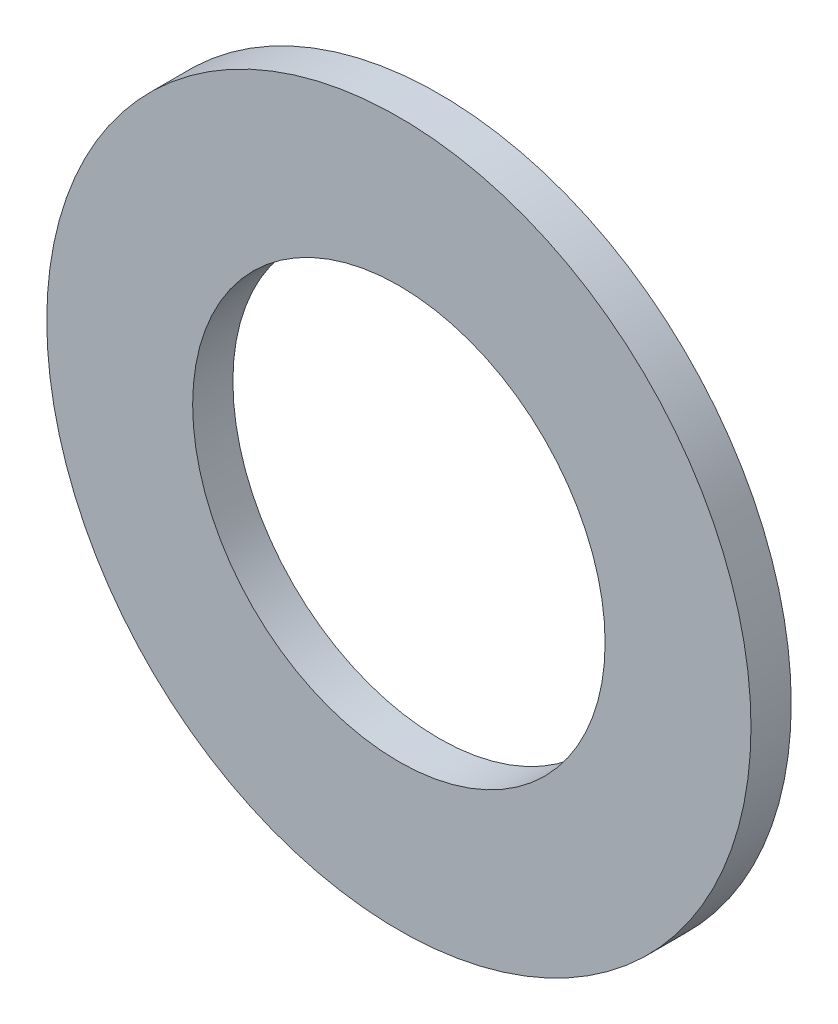
SolidWorks part; units mm, degrees
material "ABS"
ref_plane "Front Plane" through (0, 0, 0) normal (0, 0, 1) x (1, 0, 0)
ref_plane "Top Plane" through (0, 0, 0) normal (0, 1, 0) x (1, 0, 0)
ref_plane "Right Plane" through (0, 0, 0) normal (1, 0, 0) x (0, 0, -1)
sketch "Sketch1" plane through (0, 0, 0) normal (0, 0, 1) x (1, 0, 0)
  circle A0 centre (0, 0) radius 4.1
  circle A1 centre (0, 0) radius 7
  dimension "D1" = 8.2
  dimension "D2" = 14
extrude "Boss-Extrude1" add sketch "Sketch1" along normal blind 0.8
equation "\"D1@Sketch1\"=8+\"print_fit@Parameters@Parameters.SLDPRT\""
